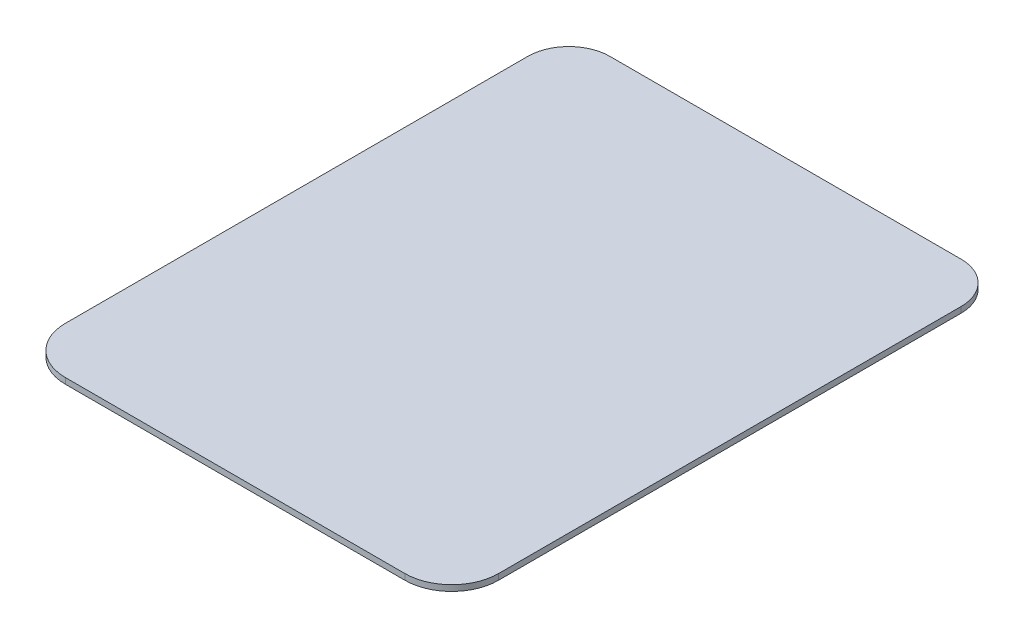
SolidWorks part; units mm, degrees
ref_plane "Ebene vorne" through (0, 0, 0) normal (0, 0, 1) x (1, 0, 0)
ref_plane "Ebene oben" through (0, 0, 0) normal (0, 1, 0) x (1, 0, 0)
ref_plane "Ebene rechts" through (0, 0, 0) normal (1, 0, 0) x (0, 0, -1)
sketch "Skizze1" plane through (0, 0, 0) normal (0, 1, 0) x (1, 0, 0)
  line L0 (0, 47) -> (0, -47) construction
  line L1 (-30, 47) -> (30, 47)
  line L2 (-37, 40) -> (-37, -39)
  line L3 (-29, -47) -> (29, -47)
  line L4 (37, 40) -> (37, -39)
  arc A0 (29, -47) -> (37, -39) centre (29, -39) ccw
  arc A1 (-29, -47) -> (-37, -39) centre (-29, -39) cw
  arc A2 (37, 40) -> (30, 47) centre (30, 40) ccw
  arc A3 (-37, 40) -> (-30, 47) centre (-30, 40) cw
  point P6 (0, 0)
  point P12 (-37, -47)
  point P15 (37, 47)
  point P18 (-37, 47)
  dimension "D3" = 8
  dimension "D4" = 7
  dimension "D1" = 74
  dimension "D2" = 94
extrude "Aufsatz-Linear austragen1" add sketch "Skizze1" along normal blind 1
